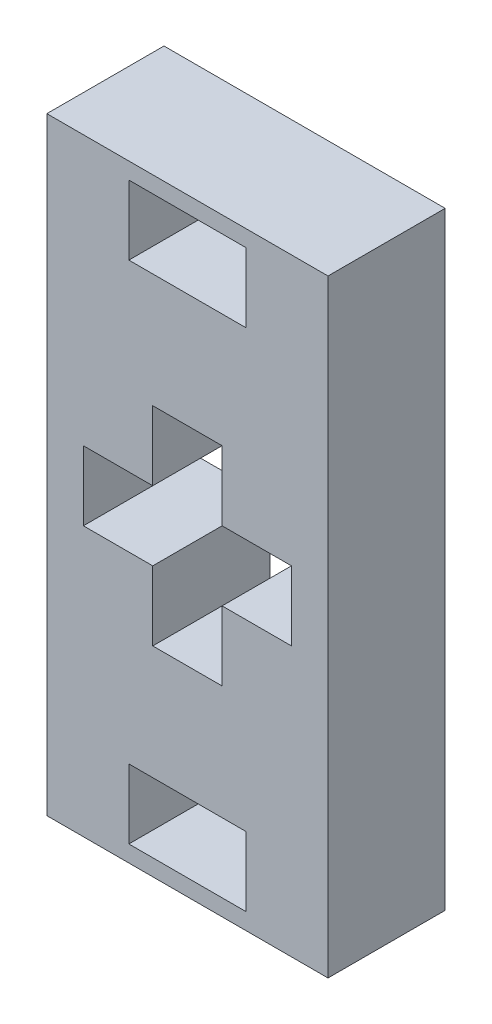
SolidWorks part; units mm, degrees
ref_plane "Front Plane" through (0, 0, 0) normal (0, 0, 1) x (1, 0, 0)
ref_plane "Top Plane" through (0, 0, 0) normal (0, 1, 0) x (1, 0, 0)
ref_plane "Right Plane" through (0, 0, 0) normal (1, 0, 0) x (0, 0, -1)
sketch "Sketch1" plane through (0, 0, 0) normal (0, 0, 1) x (1, 0, 0)
  line L1 (0, 16.477) -> (7.62, 16.477)
  line L2 (0, 16.477) -> (0, 0)
  line L3 (0, 0) -> (7.62, 0)
  line L4 (7.62, 16.477) -> (7.62, 0)
  dimension "D1" = 16.477
  dimension "D2" = 7.62
extrude "Boss-Extrude1" add sketch "Sketch1" along normal blind 3.175
sketch "Sketch2" plane through (0, 0, 3.175) normal (0, 0, 1) x (1, 0, 0)
  line L0 (3.81, 16.477) -> (3.81, 0) construction
  line L1 (7.62, 0) -> (7.62, 16.477) construction
  line L2 (0, 0) -> (7.62, 0) construction
  line L3 (7.62, 16.477) -> (0, 16.477) construction
  line L4 (2.8702, 11.0579) -> (4.7498, 11.0579)
  line L5 (4.7498, 11.0579) -> (4.7498, 9.1783)
  line L6 (4.7498, 9.1783) -> (6.6294, 9.1783)
  line L7 (6.6294, 9.1783) -> (6.6294, 7.2987)
  line L8 (6.6294, 7.2987) -> (4.7498, 7.2987)
  line L9 (4.7498, 7.2987) -> (4.7498, 5.4191)
  line L10 (4.7498, 5.4191) -> (2.8702, 5.4191)
  line L11 (0.9906, 7.2987) -> (0.9906, 9.1783)
  line L12 (2.8702, 9.1783) -> (0.9906, 9.1783)
  line L13 (2.8702, 5.4191) -> (2.8702, 7.2987)
  line L14 (0.9906, 7.2987) -> (2.8702, 7.2987)
  line L15 (2.8702, 9.1783) -> (2.8702, 11.0579)
  line L16 (0, 8.2385) -> (7.62, 8.2385) construction
  line L17 (0, 16.477) -> (0, 0) construction
  line L18 (2.2225, 16.0301) -> (2.2225, 14.1505)
  line L19 (5.3975, 16.0301) -> (5.3975, 14.1505)
  line L20 (2.2225, 16.0301) -> (5.3975, 16.0301)
  line L21 (2.2225, 14.1505) -> (5.3975, 14.1505)
  line L22 (2.2225, 2.3268) -> (2.2225, 0.4472)
  line L23 (5.3975, 2.3268) -> (5.3975, 0.4472)
  line L24 (2.2225, 2.3268) -> (5.3975, 2.3268)
  line L25 (2.2225, 0.4472) -> (5.3975, 0.4472)
  line L26 (3.81, 14.1505) -> (3.81, 2.3268) construction
  point P15 (3.81, 11.0579)
  point P19 (0.9906, 8.2385)
  point P23 (6.6294, 8.2385)
  point P37 (3.81, 0.4472)
  point P38 (3.81, 16.0301)
  dimension "D1" = 1.8796
  dimension "D2" = 3.175
  dimension "D3" = 11.8237
  dimension "D4" = 0.4472
extrude "Cut-Extrude1" cut sketch "Sketch2" against normal up to surface (3.175 mm away) up to face at (3.81, 8.2385, 0)
